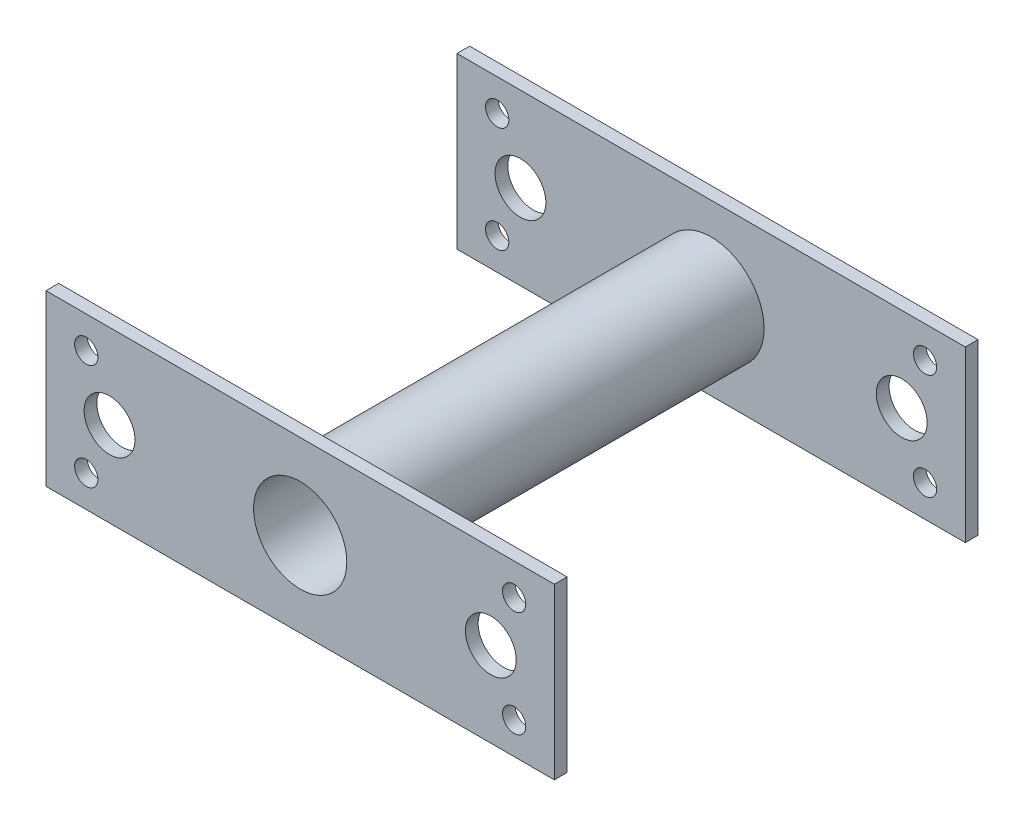
SolidWorks part; units mm, degrees
ref_plane "前视基准面" through (0, 0, 0) normal (0, 0, 1) x (1, 0, 0)
ref_plane "上视基准面" through (0, 0, 0) normal (0, 1, 0) x (1, 0, 0)
ref_plane "右视基准面" through (0, 0, 0) normal (1, 0, 0) x (0, 0, -1)
sketch "草图1" plane through (0, 0, 0) normal (0, 0, 1) x (1, 0, 0)
  line L1 (-60, 20) -> (60, 20)
  line L2 (-60, 20) -> (-60, -20)
  line L3 (-60, -20) -> (60, -20)
  line L4 (60, 20) -> (60, -20)
  dimension "D1" = 120
  dimension "D2" = 40
  dimension "D3" = 60
  dimension "D4" = 20
extrude "凸台-拉伸1" add sketch "草图1" along normal blind 3
sketch "草图2" plane through (0, 0, 3) normal (0, 0, 1) x (1, 0, 0)
  circle A0 centre (0, 0) radius 12.5
  dimension "D1" = 25
extrude "凸台-拉伸2" add sketch "草图2" along normal blind 94
sketch "草图3" plane through (0, 0, 97) normal (0, 0, 1) x (1, 0, 0)
  line L1 (-60, 20) -> (60, 20)
  line L2 (-60, 20) -> (-60, -20)
  line L3 (-60, -20) -> (60, -20)
  line L4 (60, 20) -> (60, -20)
extrude "凸台-拉伸3" add sketch "草图3" along normal blind 3
sketch "草图4" plane through (0, 0, 100) normal (0, 0, 1) x (1, 0, 0)
  circle A0 centre (0, 0) radius 11
  dimension "D1" = 22
extrude "切除-拉伸1" cut sketch "草图4" against normal through all and the other way through all
sketch "草图5" plane through (0, 0, 100) normal (0, 0, 1) x (1, 0, 0)
  line L1 (-50.5, 12.5) -> (50.5, 12.5) construction
  line L2 (-50.5, 12.5) -> (-50.5, -12.5) construction
  line L3 (-50.5, -12.5) -> (50.5, -12.5) construction
  line L4 (50.5, 12.5) -> (50.5, -12.5) construction
  circle A0 centre (-50.5, 12.5) radius 2.75
  circle A1 centre (-50.5, -12.5) radius 2.75
  circle A2 centre (50.5, 12.5) radius 2.75
  circle A3 centre (50.5, -12.5) radius 2.75
  dimension "D5" = 5.5
  dimension "D1" = 101
  dimension "D2" = 25
  dimension "D3" = 50.5
  dimension "D4" = 12.5
extrude "切除-拉伸2" cut sketch "草图5" against normal through all
sketch "草图6" plane through (0, 0, 100) normal (0, 0, 1) x (1, 0, 0)
  line L0 (0, 0) -> (0, 50000) construction
  circle A0 centre (45, 0) radius 6
  circle A1 centre (-45, 0) radius 6
  dimension "D1" = 12
  dimension "D2" = 45
extrude "切除-拉伸3" cut sketch "草图6" against normal through all
